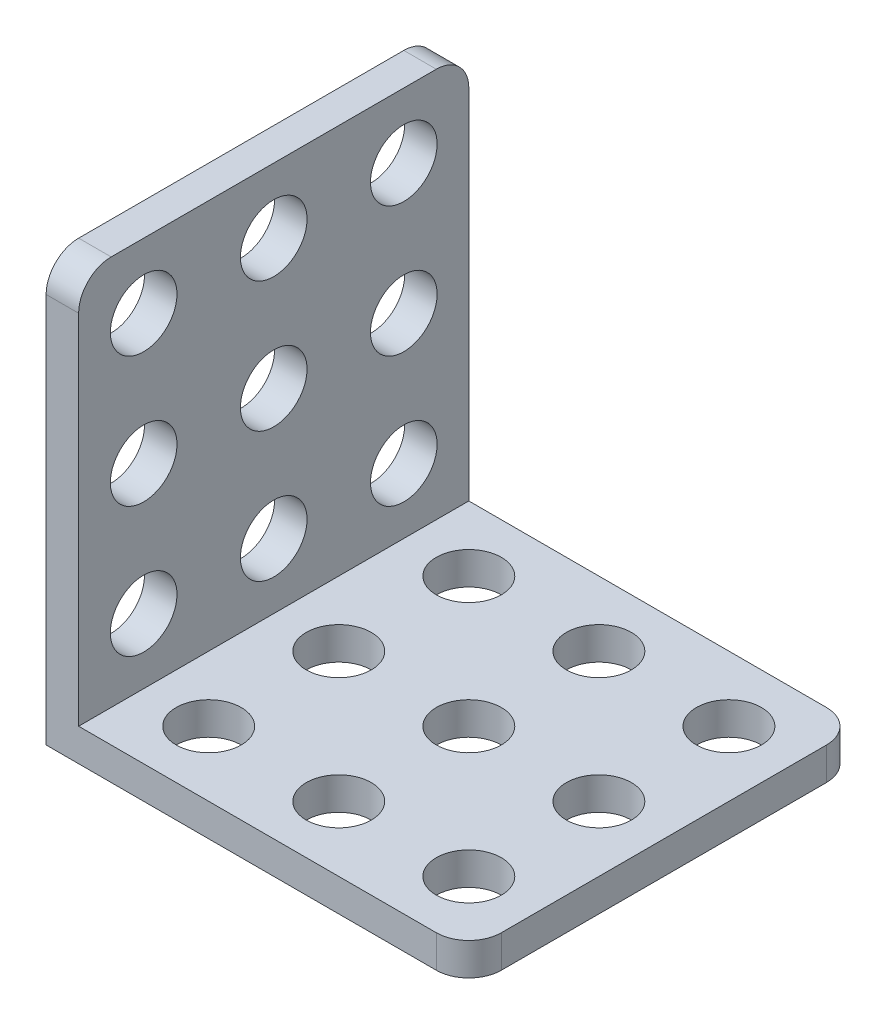
SolidWorks part; units mm, degrees
ref_plane "Front Plane" through (0, 0, 0) normal (0, 0, 1) x (1, 0, 0)
ref_plane "Top Plane" through (0, 0, 0) normal (0, 1, 0) x (1, 0, 0)
ref_plane "Right Plane" through (0, 0, 0) normal (1, 0, 0) x (0, 0, -1)
sketch "Sketch1" plane through (0, 0, 0) normal (0, 0, 1) x (1, 0, 0)
  line L0 (0, 0) -> (0, 26)
  line L1 (0, 26) -> (2, 26)
  line L2 (2, 26) -> (2, 2)
  line L3 (2, 2) -> (26, 2)
  line L4 (26, 2) -> (26, 0)
  line L5 (26, 0) -> (0, 0)
  dimension "D1" = 26
  dimension "D2" = 26
  dimension "D3" = 2
  dimension "D4" = 2
extrude "Boss-Extrude1" add sketch "Sketch1" along normal blind 24
sketch "Sketch2" plane through (2, 0, 0) normal (1, 0, 0) x (0, 0, -1)
  line L0 (-24, 26) -> (0, 26) construction
  circle A0 centre (-20, 22) radius 2.05
  point P4 (-12, 26)
  dimension "D1" = 4.1
  dimension "D2" = 8
  dimension "D3" = 4
extrude "Cut-Extrude1" cut sketch "Sketch2" against normal through all
pattern_linear "LPattern1" count 3 spacing 8 along (0, 0, -1) count 3 spacing 8 along (0, -1, 0) of "Cut-Extrude1"
sketch "Sketch3" plane through (0, 2, 0) normal (0, 1, 0) x (1, 0, 0)
  line L0 (26, 0) -> (2, 0) construction
  line L1 (26, -24) -> (26, 0) construction
  circle A0 centre (22, -4) radius 2
  dimension "D1" = 4
  dimension "D2" = 4
  dimension "D3" = 4
extrude "Cut-Extrude2" cut sketch "Sketch3" against normal through all
pattern_linear "LPattern2" count 3 spacing 8 along (0, 0, 1) count 3 spacing 8 along (-1, 0, 0) of "Cut-Extrude2"
fillet "Fillet1" radius 2 4 edges at (1, 26, 24) (1, 26, 0) (26, 1, 0) (26, 1, 24)
